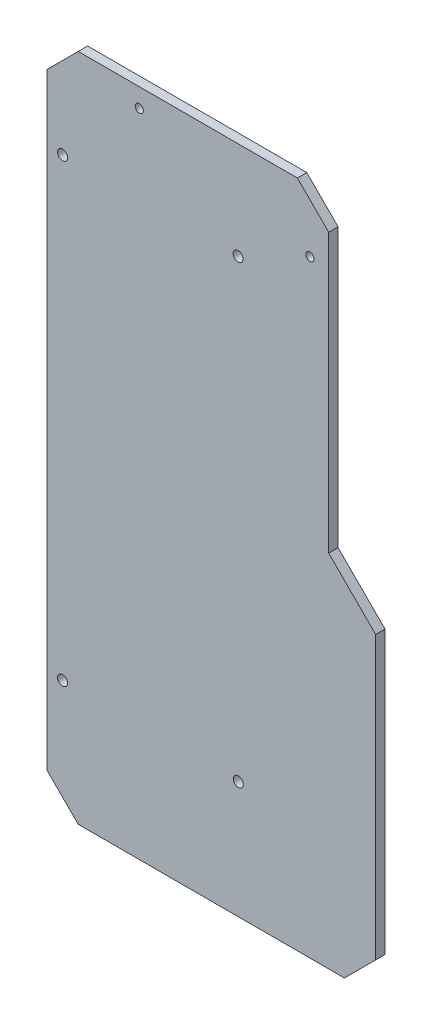
SolidWorks part; units mm, degrees
ref_plane "Front Plane" through (0, 0, 0) normal (0, 0, 1) x (1, 0, 0)
ref_plane "Top Plane" through (0, 0, 0) normal (0, 1, 0) x (1, 0, 0)
ref_plane "Right Plane" through (0, 0, 0) normal (1, 0, 0) x (0, 0, -1)
sketch "Sketch1" plane through (0, 0, 0) normal (0, 0, 1) x (1, 0, 0)
  line L0 (-80, -0.7565) -> (-80, 4.2435) construction
  line L1 (-70, 34.0035) -> (0, 34.0035)
  line L2 (-80, 24.0035) -> (-80, -169.754)
  line L3 (-70, -179.754) -> (0, -179.754)
  line L6 (-13.5618, -149.754) -> (-80, -149.754) construction
  line L8 (10, -64.754) -> (10, 24.0035)
  line L9 (-80, 24.0035) -> (-70, 34.0035)
  line L10 (10, 24.0035) -> (0, 34.0035)
  line L11 (-80, -169.754) -> (-70, -179.754)
  line L13 (10, -64.754) -> (25, -79.754)
  line L14 (25, -79.754) -> (25, -169.754)
  line L15 (15, -179.754) -> (0, -179.754)
  line L16 (25, -169.754) -> (15, -179.754)
  line L17 (-80, 10.2435) -> (-13.0607, 10.2435) construction
  circle A0 centre (-75, 2.8935) radius 1.6
  circle A1 centre (-18.9466, 2.8935) radius 1.6
  circle A2 centre (-75, -142.404) radius 1.6
  circle A3 centre (-18.8932, -142.404) radius 1.6
  circle A6 centre (4, 14.2435) radius 1.3
  circle A7 centre (-50.5, 28.0035) radius 1.3
  point P0 (-80, 34.0035)
  point P2 (-80, -179.754)
  point P12 (10, 34.0035)
  point P32 (25, -179.754)
  dimension "D2" = 3.2
  dimension "D1" = 30
  dimension "D3" = 90
  dimension "D4" = 45
  dimension "D6" = 23.76
  dimension "D7" = 100
  dimension "D10" = 15
extrude "Extrude1" add sketch "Sketch1" along normal blind 3
